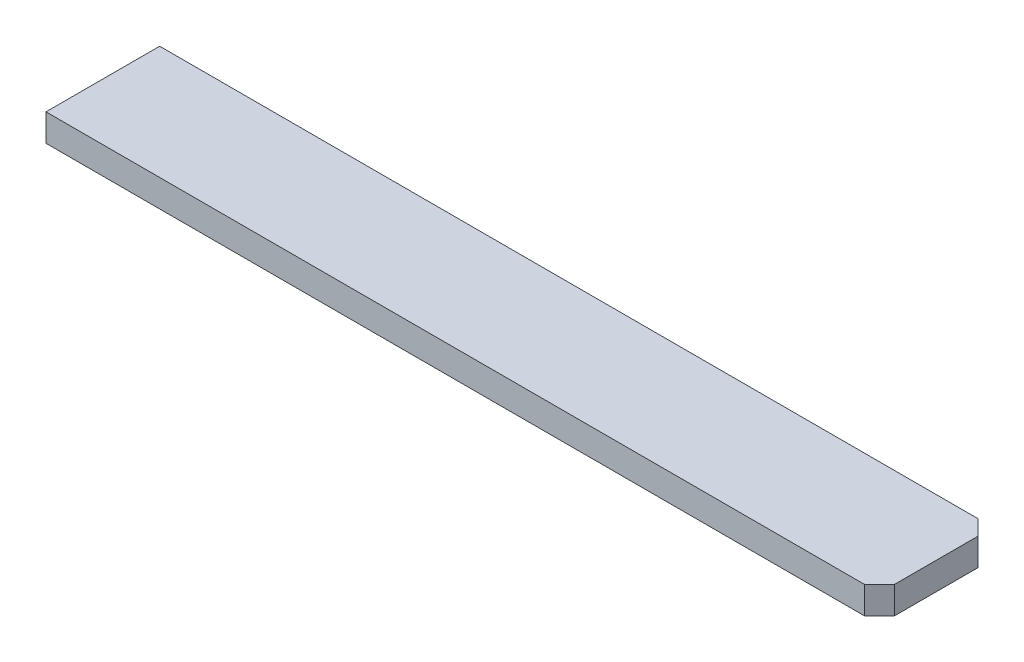
SolidWorks part; units mm, degrees
material "Pine"
ref_plane "Front Plane" through (0, 0, 0) normal (0, 0, 1) x (1, 0, 0)
ref_plane "Top Plane" through (0, 0, 0) normal (0, 1, 0) x (1, 0, 0)
ref_plane "Right Plane" through (0, 0, 0) normal (1, 0, 0) x (0, 0, -1)
sketch "Sketch1" plane through (0, 0, 0) normal (0, 0, 1) x (1, 0, 0)
  line L0 (55, 0) -> (-55, 0) construction
  line L1 (-18, 0) -> (532, 0)
  line L2 (-18, 0) -> (-18, 18)
  line L3 (-18, 18) -> (532, 18)
  line L4 (532, 0) -> (532, 18)
  line L5 (0, -55) -> (0, 55) construction
  dimension "D1" = 18
  dimension "D2" = 550
  dimension "D3" = 18
extrude "Boss-Extrude1" add sketch "Sketch1" along normal mid plane 75
sketch "Sketch2" plane through (0, 0, 0) normal (0, 0, 1) x (1, 0, 0)
  line L1 (0, 0) -> (-18, 0)
  line L2 (0, 0) -> (0, -18)
  line L3 (0, -18) -> (-18, -18)
  line L4 (-18, 0) -> (-18, -18)
  dimension "D1" = 18
  dimension "D2" = 18
extrude "Boss-Extrude2" [suppressed] add sketch "Sketch2" along normal mid plane 100 separate body
chamfer "Chamfer1" distance 10 angle 45 2 edges at (532, 9, 37.5) (532, 9, -37.5)
sketch "Sketch3" plane through (-18, 0, 0) normal (1, 0, 0) x (0, 0, -1)
  line L0 (0, 9.9) -> (0, -9.9) construction
  circle A0 centre (0, 9) radius 2
  dimension "D1" = 4
extrude "Cut-Extrude1" cut sketch "Sketch3" along normal blind 35
